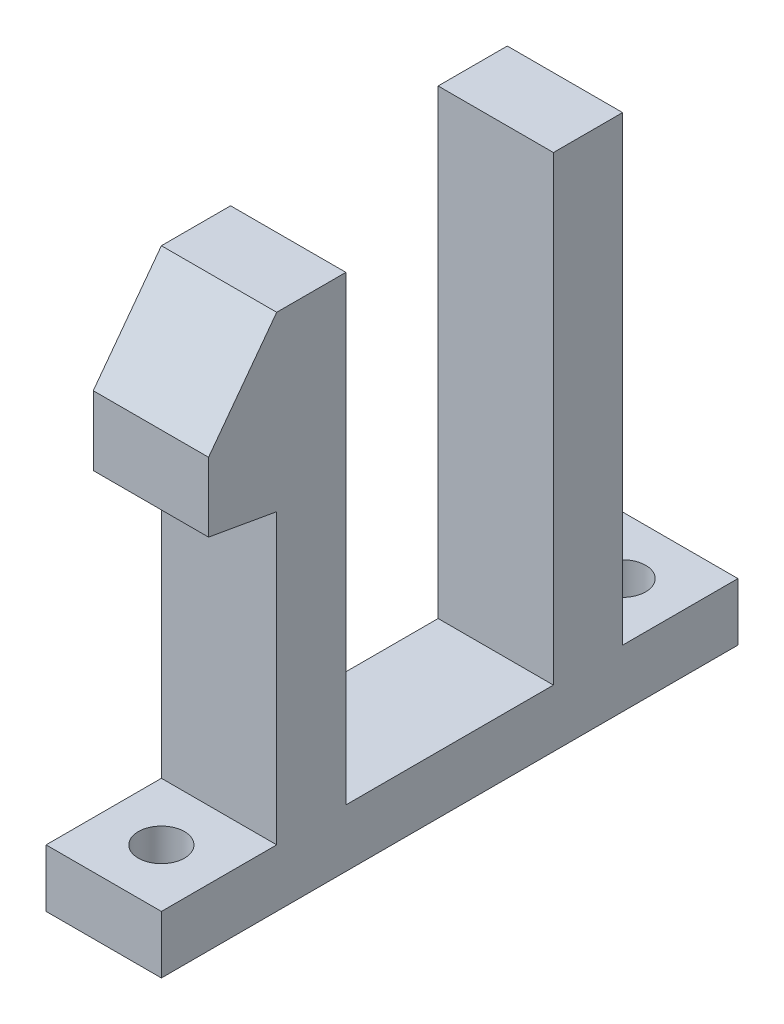
SolidWorks part; units mm, degrees
ref_plane "前视基准面" through (0, 0, 0) normal (0, 0, 1) x (1, 0, 0)
ref_plane "上视基准面" through (0, 0, 0) normal (0, 1, 0) x (1, 0, 0)
ref_plane "右视基准面" through (0, 0, 0) normal (1, 0, 0) x (0, 0, -1)
other "Configuration Table"
sketch "草图1" plane through (0, 0, 0) normal (0, 1, 0) x (1, 0, 0)
  line L0 (0, 0) -> (-5.8775, 0) construction
  line L1 (-2.5, 12.5) -> (2.5, 12.5)
  line L2 (-2.5, 12.5) -> (-2.5, -12.5)
  line L3 (-2.5, -12.5) -> (2.5, -12.5)
  line L4 (2.5, 12.5) -> (2.5, -12.5)
  line L5 (-2.5, 12.5) -> (2.5, -12.5) construction
  line L6 (-2.5, -12.5) -> (2.5, 12.5) construction
  circle A0 centre (0, 10) radius 1
  circle A1 centre (0, -10) radius 1
  point P0 (0, 0)
  dimension "D4" = 2
  dimension "D1" = 25
  dimension "D2" = 5
  dimension "D3" = 10
extrude "凸台-拉伸1" add sketch "草图1" along normal blind 2.5
sketch "草图3" plane through (0, 2.5, 0) normal (0, 1, 0) x (1, 0, 0)
  line L1 (-2.5, 7.5) -> (2.5, 7.5)
  line L2 (-2.5, 7.5) -> (-2.5, -7.5)
  line L3 (-2.5, -7.5) -> (2.5, -7.5)
  line L4 (2.5, 7.5) -> (2.5, -7.5)
  line L5 (-2.5, 7.5) -> (2.5, -7.5) construction
  line L6 (-2.5, -7.5) -> (2.5, 7.5) construction
  point P0 (0, 0)
  dimension "D1" = 15
  dimension "D2" = 5
extrude "凸台-拉伸2" add sketch "草图3" along normal blind 20
sketch "草图5" plane through (2.5, 0, 0) normal (1, 0, 0) x (0, 0, -1)
  line L0 (-7.5, 15.012) -> (-10.4544, 15.5329)
  line L1 (-7.5, 22.5) -> (-7.5, 2.5) construction
  line L4 (-10.4544, 15.5329) -> (-10.4544, 18.5329)
  line L5 (-10.4544, 18.5329) -> (-7.5, 22.5)
  line L6 (-7.5, 22.5) -> (-7.5, 15.012)
  point P4 (-7.5, 15.1135)
  point P5 (-7.5, 15.012)
  point P6 (0, 0)
  point P7 (-10.3996, 18.2697)
  point P8 (0, 0)
  point P12 (-7.5, 22.5)
  dimension "D1" = 3
  dimension "D2" = 3
  dimension "D3" = 80
sketch "草图6" plane through (2.5, 0, 0) normal (1, 0, 0) x (0, 0, -1)
  line L0 (-7.5, 22.5) -> (7.5, 22.5) construction
  line L1 (-4.5, 22.5) -> (4.5, 22.5)
  line L2 (-4.5, 22.5) -> (-4.5, 2.5)
  line L3 (-4.5, 2.5) -> (4.5, 2.5)
  line L4 (4.5, 22.5) -> (4.5, 2.5)
  line L5 (-16.1796, 2.5) -> (10.5553, 2.5) construction
  line L6 (-7.5, 22.5) -> (-7.5, 2.5) construction
  line L7 (7.5, 22.5) -> (7.5, 2.5) construction
  dimension "D1" = 3
  dimension "D2" = 3
extrude "切除-拉伸1" cut sketch "草图6" against normal through all
extrude "凸台-拉伸3" add sketch "草图5" against normal blind 5
